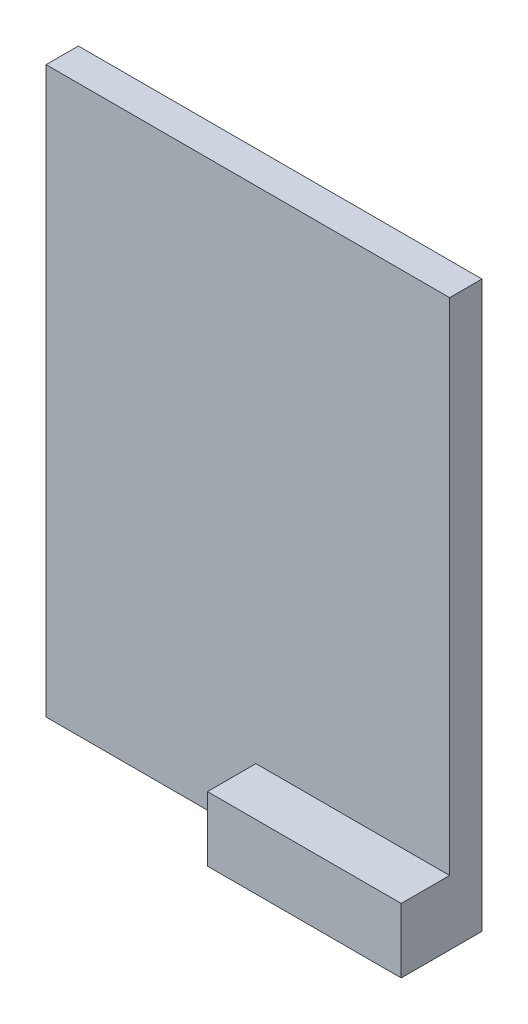
SolidWorks part; units mm, degrees
ref_plane "Alzado" through (0, 0, 0) normal (0, 0, 1) x (1, 0, 0)
ref_plane "Planta" through (0, 0, 0) normal (0, 1, 0) x (1, 0, 0)
ref_plane "Vista lateral" through (0, 0, 0) normal (1, 0, 0) x (0, 0, -1)
sketch "Croquis1" plane through (0, 0, 0) normal (0, 0, 1) x (1, 0, 0)
  line L1 (-40.6526, 11.9444) -> (-15.6526, 11.9444)
  line L2 (-40.6526, 11.9444) -> (-40.6526, -23.0556)
  line L3 (-40.6526, -23.0556) -> (-15.6526, -23.0556)
  line L4 (-15.6526, 11.9444) -> (-15.6526, -23.0556)
  dimension "D1" = 25
  dimension "D2" = 35
extrude "Saliente-Extruir1" add sketch "Croquis1" along normal blind 2
sketch "Croquis2" plane through (0, 0, 2) normal (0, 0, 1) x (1, 0, 0)
  line L1 (-15.6526, -23.0556) -> (-27.6526, -23.0556)
  line L2 (-15.6526, -23.0556) -> (-15.6526, -19.0556)
  line L3 (-15.6526, -19.0556) -> (-27.6526, -19.0556)
  line L4 (-27.6526, -23.0556) -> (-27.6526, -19.0556)
  dimension "D1" = 4
  dimension "D2" = 12
extrude "Saliente-Extruir2" add sketch "Croquis2" along normal blind 3
